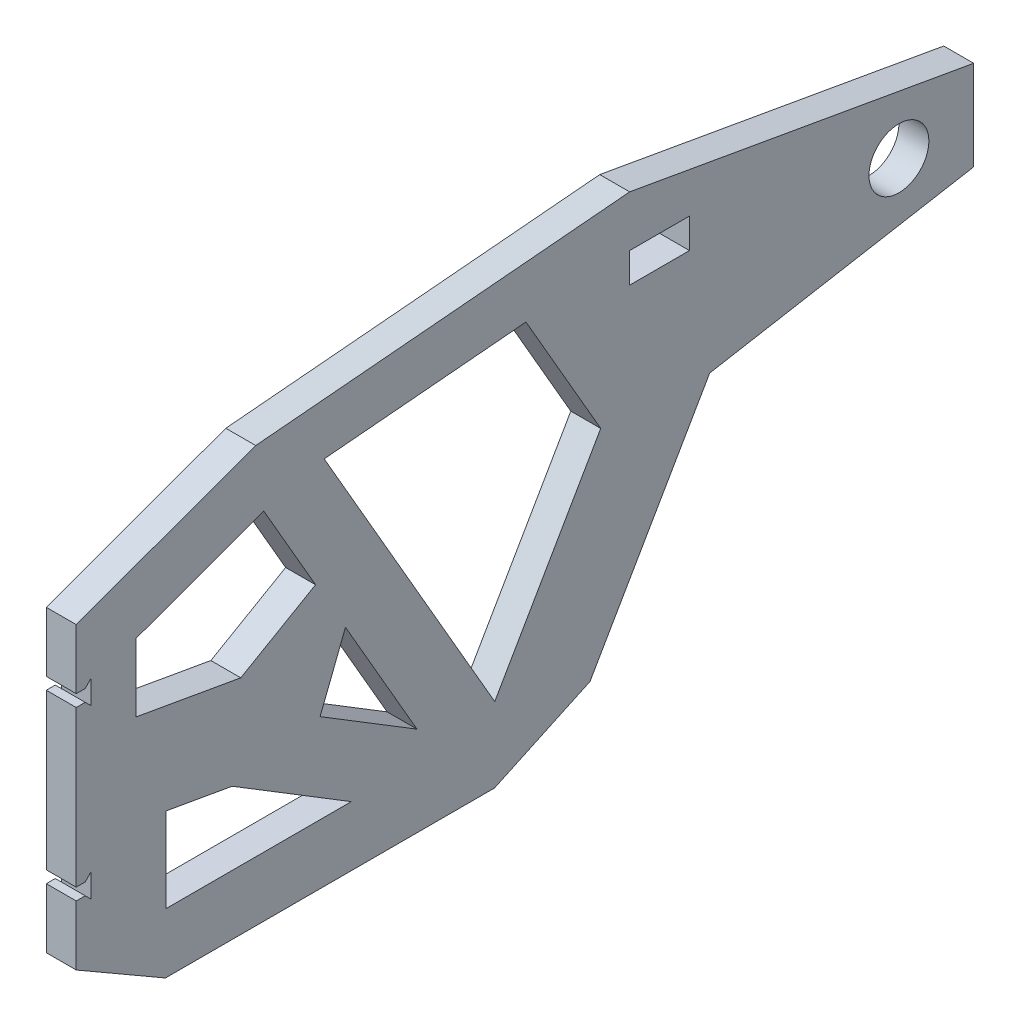
SolidWorks part; units mm, degrees
ref_plane "Plan de face" through (0, 0, 0) normal (0, 0, 1) x (1, 0, 0)
ref_plane "Plan de dessus" through (0, 0, 0) normal (0, 1, 0) x (1, 0, 0)
ref_plane "Plan de droite" through (0, 0, 0) normal (1, 0, 0) x (0, 0, -1)
sketch "Esquisse1" plane through (0, 0, 0) normal (1, 0, 0) x (0, 0, -1)
  line L30 (0, 0) -> (300, 0)
  line L31 (0, 0) -> (0, 150)
  line L32 (0, 150) -> (300, 150)
  line L33 (300, 0) -> (300, 150)
  dimension "D1" = 300
  dimension "D2" = 150
extrude "Boss.-Extru.1" add sketch "Esquisse1" along normal mid plane 10 contours L32 L33 L30 L31
sketch "Esquisse2" plane through (0, 0, 0) normal (1, 0, 0) x (0, 0, -1)
  line L0 (0, 117.2257) -> (60, 139.0639)
  line L3 (0, 0) -> (0, 150) construction
  line L4 (60, 139.0639) -> (185, 150)
  line L5 (0, 150) -> (300, 150) construction
  line L6 (185, 150) -> (300, 129.7224)
  line L7 (300, 0) -> (300, 150) construction
  line L8 (300, 129.7224) -> (300, 99.7224)
  line L9 (300, 99.7224) -> (211.742, 84.1601)
  line L10 (211.742, 84.1601) -> (171.742, 14.8781)
  line L11 (171.742, 14.8781) -> (139.8358, 0)
  line L12 (0, 0) -> (300, 0) construction
  line L13 (139.8358, 0) -> (29.8358, 0)
  line L14 (29.8358, 0) -> (0, 17.2257)
  line L15 (0, 17.2257) -> (0, 117.2257)
  dimension "D1" = 15
  dimension "D2" = 5
  dimension "D3" = 10
  dimension "D4" = 30
  dimension "D5" = 10
  dimension "D6" = 30
  dimension "D7" = 25
  dimension "D8" = 100
  dimension "D9" = 115
  dimension "D10" = 60
  dimension "D11" = 40
  dimension "D12" = 110
extrude "Enlèv. mat.-Extru.1" cut sketch "Esquisse2" against normal mid plane 10 flip side to cut
sketch "Esquisse3" plane through (5, 0, 0) normal (1, 0, 0) x (0, 0, -1)
  line L0 (20, 103.2216) -> (20, 80.4933)
  line L1 (20, 80.4933) -> (55, 74.3219)
  line L2 (55, 74.3219) -> (80, 88.7556)
  line L3 (80, 88.7556) -> (62.6795, 118.7556)
  line L4 (62.6795, 118.7556) -> (20, 103.2216)
  line L5 (60, 139.0639) -> (0, 117.2257) construction
  line L6 (0, 17.2257) -> (0, 117.2257) construction
  line L7 (90, 71.4351) -> (113.9226, 30)
  line L8 (113.9226, 30) -> (81.5081, 49.8318)
  line L9 (81.5081, 49.8318) -> (90, 71.4351)
  line L10 (29.8358, 0) -> (139.8358, 0) construction
  line L11 (82.8868, 123.7556) -> (139.9033, 25)
  line L12 (139.9033, 25) -> (175.3264, 86.3546)
  line L13 (175.3264, 86.3546) -> (150.3264, 129.6558)
  line L14 (150.3264, 129.6558) -> (82.8868, 123.7556)
  line L16 (185, 150) -> (60, 139.0639) construction
  line L17 (171.742, 14.8781) -> (211.742, 84.1601) construction
  line L18 (91.945, 20) -> (30, 20)
  line L19 (30, 20) -> (30, 48.2672)
  line L20 (30, 48.2672) -> (52.1171, 44.3674)
  line L21 (52.1171, 44.3674) -> (91.945, 20)
  point P20 (33.3599, 19.3507)
  dimension "D1" = 20
  dimension "D2" = 20
  dimension "D3" = 100
  dimension "D4" = 140
  dimension "D5" = 60
  dimension "D6" = 35
  dimension "D7" = 30
  dimension "D8" = 100
  dimension "D9" = 30
  dimension "D10" = 20
  dimension "D11" = 100
  dimension "D12" = 38
  dimension "D13" = 5
  dimension "D14" = 20
  dimension "D15" = 5
  dimension "D16" = 50
  dimension "D17" = 30
  dimension "D18" = 20
  dimension "D19" = 20
  dimension "D20" = 30
extrude "Enlèv. mat.-Extru.2" cut sketch "Esquisse3" against normal through all both and the other way through all
sketch "Esquisse4" plane through (5, 0, 0) normal (1, 0, 0) x (0, 0, -1)
  line L0 (0, 97.2257) -> (3, 97.2257)
  line L1 (0, 17.2257) -> (0, 117.2257) construction
  line L2 (3, 97.2257) -> (5, 99.2257)
  line L3 (5, 99.2257) -> (5, 91.2257)
  line L4 (5, 91.2257) -> (3, 93.2257)
  line L5 (3, 93.2257) -> (0, 93.2257)
  line L6 (-59.63, 67.2257) -> (152.1394, 67.2257) construction
  line L7 (3, 41.2257) -> (0, 41.2257)
  line L8 (5, 43.2257) -> (3, 41.2257)
  line L9 (5, 35.2257) -> (5, 43.2257)
  line L10 (3, 37.2257) -> (5, 35.2257)
  line L11 (0, 37.2257) -> (3, 37.2257)
  line L12 (0, 97.2257) -> (0, 93.2257)
  line L13 (0, 41.2257) -> (0, 37.2257)
  point P11 (0, 67.2257)
  dimension "D1" = 5
  dimension "D2" = 45
  dimension "D3" = 4
  dimension "D4" = 20
  dimension "D5" = 3
extrude "Enlèv. mat.-Extru.3" cut sketch "Esquisse4" against normal through all both and the other way through all
sketch "Esquisse5" plane through (-5, 0, 0) normal (-1, 0, 0) x (0, 0, 1)
  line L0 (-300, 99.7224) -> (-300, 129.7224) construction
  circle A0 centre (-275, 114.7224) radius 10
  point P2 (0, 0)
  point P5 (-300, 114.7224)
  dimension "D1" = 20
  dimension "D2" = 25
extrude "Enlèv. mat.-Extru.4" cut sketch "Esquisse5" against normal through all both
sketch "Esquisse6" plane through (5, 0, 0) normal (1, 0, 0) x (0, 0, -1)
  line L1 (185, 133) -> (205, 133)
  line L2 (185, 133) -> (185, 123)
  line L3 (185, 123) -> (205, 123)
  line L4 (205, 133) -> (205, 123)
  point P4 (185, 128)
  dimension "D1" = 20
  dimension "D2" = 10
  dimension "D3" = 17
extrude "Enlèv. mat.-Extru.5" cut sketch "Esquisse6" against normal blind 49
